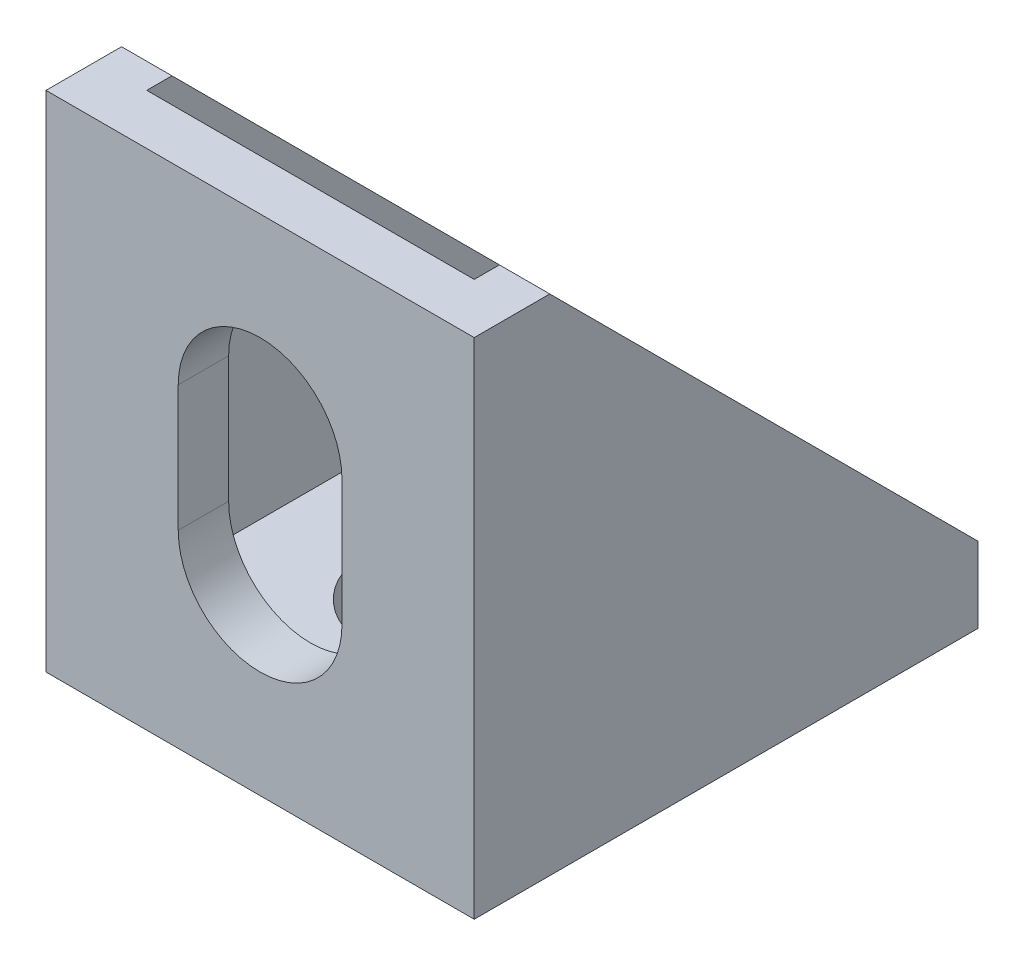
SolidWorks part; units mm, degrees
ref_plane "Front Plane" through (0, 0, 0) normal (0, 0, 1) x (1, 0, 0)
ref_plane "Top Plane" through (0, 0, 0) normal (0, 1, 0) x (1, 0, 0)
ref_plane "Right Plane" through (0, 0, 0) normal (1, 0, 0) x (0, 0, -1)
sketch "Sketch1" plane through (0, 0, 0) normal (1, 0, 0) x (0, 0, -1)
  line L0 (3, 20) -> (0, 20)
  line L1 (0, 20) -> (0, 0)
  line L2 (0, 0) -> (20, 0)
  line L3 (20, 0) -> (20, 3)
  line L4 (20, 3) -> (3, 20)
  dimension "D1" = 3
  dimension "D2" = 20
extrude "Body" add sketch "Sketch1" along normal mid plane 17
sketch "Sketch2" plane through (0, 0, -20) normal (0, 0, -1) x (-1, 0, 0)
  line L0 (-8.5, 3) -> (8.5, 3) construction
  line L1 (-6.5, 3) -> (6.5, 3)
  line L2 (-6.5, 3) -> (-6.5, 20)
  line L3 (-6.5, 20) -> (6.5, 20)
  line L4 (6.5, 3) -> (6.5, 20)
  line L5 (-8.5, 20) -> (8.5, 20) construction
  line L6 (8.5, 3) -> (8.5, 20) construction
  dimension "D1" = 2
  dimension "D2" = 2
extrude "Extusion" cut sketch "Sketch2" against normal offset from surface (18 mm away) 2 up to face at (0, 10, 0)
sketch "Sketch3" plane through (0, 0, -2) normal (0, 0, -1) x (-1, 0, 0)
  line L0 (0, 7.5) -> (0, 12.5) construction
  line L1 (-3.25, 7.5) -> (-3.25, 12.5)
  line L2 (3.25, 7.5) -> (3.25, 12.5)
  line L3 (-6.5, 20) -> (6.5, 20) construction
  arc A0 (-3.25, 7.5) -> (3.25, 7.5) centre (0, 7.5) ccw
  arc A1 (3.25, 12.5) -> (-3.25, 12.5) centre (0, 12.5) ccw
  point P2 (0, 10)
  point P7 (-8.2602, 9.1206)
  point P8 (0, 0)
  dimension "D1" = 6.5
  dimension "D2" = 5
  dimension "D3" = 10
extrude "Hole_A" cut sketch "Sketch3" against normal through all
sketch "Sketch4" plane through (0, 3, 0) normal (0, 1, 0) x (1, 0, 0)
  line L0 (0, 7.5) -> (0, 12.5) construction
  line L1 (-3.25, 7.5) -> (-3.25, 12.5)
  line L2 (3.25, 7.5) -> (3.25, 12.5)
  line L4 (6.5, 20) -> (-6.5, 20) construction
  arc A0 (-3.25, 7.5) -> (3.25, 7.5) centre (0, 7.5) ccw
  arc A1 (3.25, 12.5) -> (-3.25, 12.5) centre (0, 12.5) ccw
  point P3 (0, 10)
  dimension "D1" = 6.5
  dimension "D2" = 5
  dimension "D3" = 10
extrude "Hole_B" cut sketch "Sketch4" against normal blind 17
